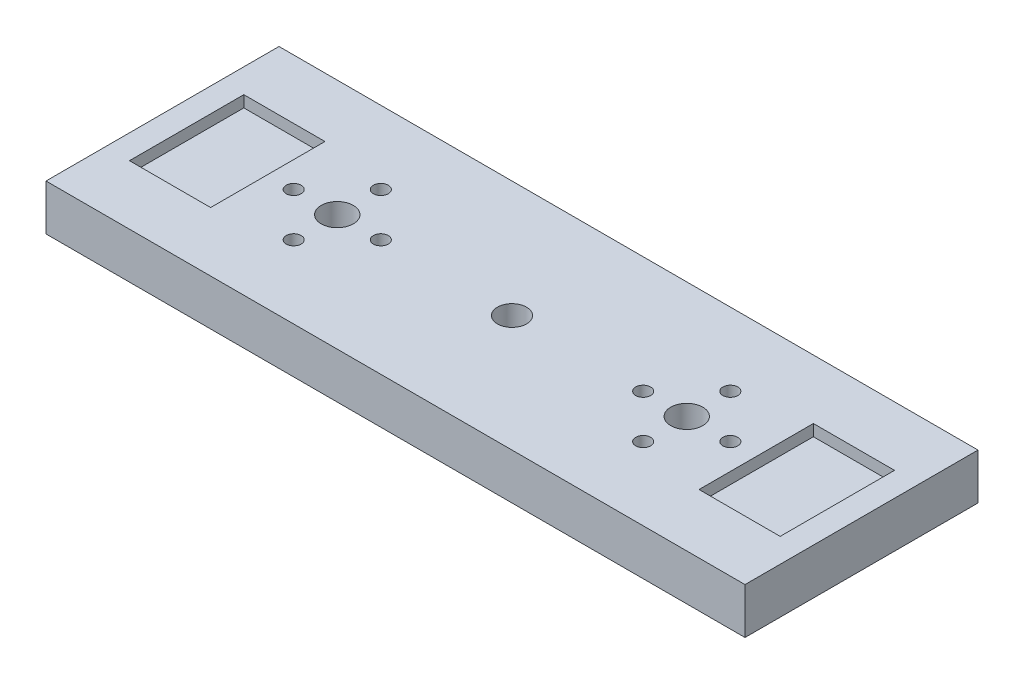
SolidWorks part; units mm, degrees
material "FEA Aluminum"
ref_plane "Front Plane" through (0, 0, 0) normal (0, 0, 1) x (1, 0, 0)
ref_plane "Top Plane" through (0, 0, 0) normal (0, 1, 0) x (1, 0, 0)
ref_plane "Right Plane" through (0, 0, 0) normal (1, 0, 0) x (0, 0, -1)
sketch "Sketch2" plane through (0, 0, 0) normal (0, 1, 0) x (1, 0, 0)
  line L1 (152.4, 50.8) -> (-152.4, 50.8)
  line L2 (152.4, 50.8) -> (152.4, -50.8)
  line L3 (152.4, -50.8) -> (-152.4, -50.8)
  line L4 (-152.4, 50.8) -> (-152.4, -50.8)
  line L5 (152.4, 50.8) -> (-152.4, -50.8) construction
  line L6 (152.4, -50.8) -> (-152.4, 50.8) construction
  circle A0 centre (0, 0) radius 6.35
  circle A1 centre (-76.2, 0) radius 7
  circle A2 centre (76.2, 0) radius 7
  point P0 (0, 0)
  dimension "D3" = 12.7
  dimension "D4" = 14
  dimension "D1" = 304.8
  dimension "D2" = 101.6
  dimension "D5" = 76.2
  dimension "D6" = 76.2
extrude "Boss-Extrude1" add sketch "Sketch2" along normal blind 20
sketch "Sketch3" plane through (0, 20, 0) normal (0, 1, 0) x (1, 0, 0)
  circle A0 centre (-76.2, 0) radius 19 construction
  circle A1 centre (-76.2, 19) radius 3.25
  dimension "D1" = 38
  dimension "D2" = 6.5
extrude "Cut-Extrude1" cut sketch "Sketch3" against normal through all
pattern_circular "CirPattern1" count 4 over 360 about axis through (-76.2, 0, 0) along (0, 1, 0) of "Cut-Extrude1"
pattern_linear "LPattern1" count 2 spacing 152.4 along (1, 0, 0) of "CirPattern1", "Cut-Extrude1"
sketch "Sketch4" plane through (0, 20, 0) normal (0, 1, 0) x (1, 0, 0)
  line L1 (-141.8727, 24.9323) -> (-106.485, 24.9323)
  line L2 (-141.8727, 24.9323) -> (-141.8727, -24.9323)
  line L3 (-141.8727, -24.9323) -> (-106.485, -24.9323)
  line L4 (-106.485, 24.9323) -> (-106.485, -24.9323)
  line L5 (-141.8727, 24.9323) -> (-106.485, -24.9323) construction
  line L6 (-141.8727, -24.9323) -> (-106.485, 24.9323) construction
  line L7 (0, 61.5341) -> (0, -69.584) construction
  line L8 (106.485, 24.9323) -> (106.485, -24.9323)
  line L9 (141.8727, -24.9323) -> (106.485, -24.9323)
  line L10 (141.8727, 24.9323) -> (106.485, 24.9323)
  line L11 (141.8727, 24.9323) -> (141.8727, -24.9323)
  point P0 (-124.1789, 0)
extrude "Cut-Extrude2" cut sketch "Sketch4" against normal blind 5
equation "\"Length\"= 304.8"
equation "\"Width\"= 101.6"
equation "\"t\"= 20"
equation "\"Spacing\"= 152.4"
equation "\"Offset\"= 76.2"
equation "\"D1@Sketch2\"=\"Length\""
equation "\"D6@Sketch2\"=\"Offset\""
equation "\"D5@Sketch2\"=\"Offset\""
